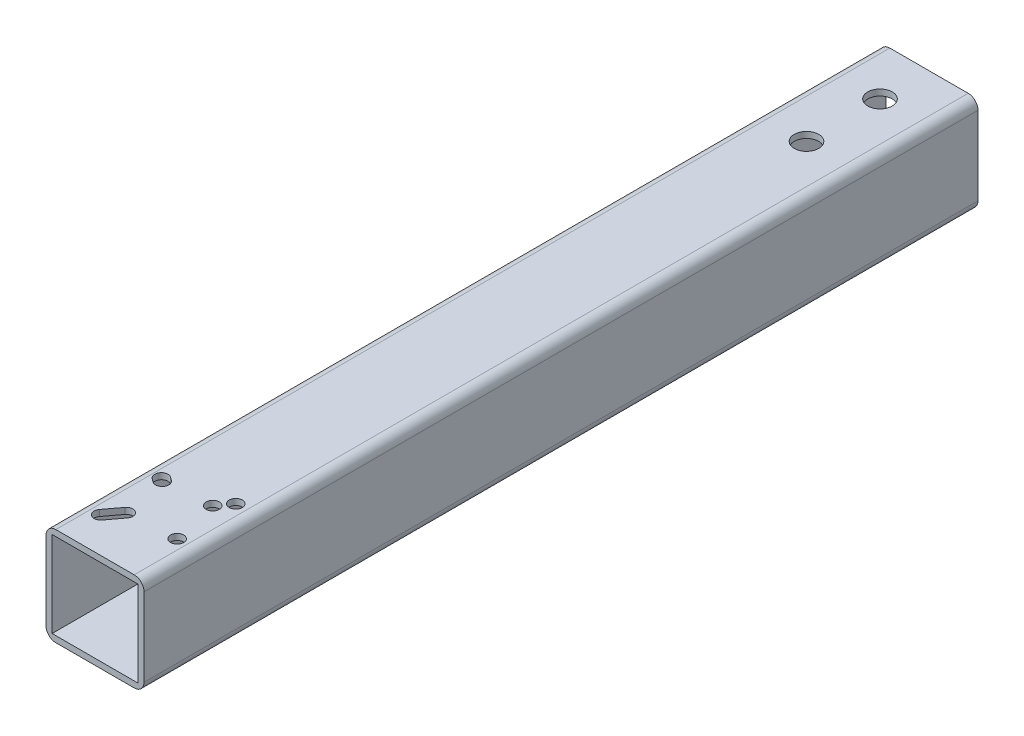
SolidWorks part; units mm, degrees
ref_plane "Front Plane" through (0, 0, 0) normal (0, 0, 1) x (1, 0, 0)
ref_plane "Top Plane" through (0, 0, 0) normal (0, 1, 0) x (1, 0, 0)
ref_plane "Right Plane" through (0, 0, 0) normal (1, 0, 0) x (0, 0, -1)
sketch "Sketch1" plane through (0, 0, 0) normal (0, 0, 1) x (1, 0, 0)
  line L1 (-24.2596, 11.4248) -> (1.1404, 11.4248)
  line L2 (-24.2596, 11.4248) -> (-24.2596, -13.9752)
  line L3 (-24.2596, -13.9752) -> (1.1404, -13.9752)
  line L4 (1.1404, 11.4248) -> (1.1404, -13.9752)
  line L5 (-22.6721, 9.8373) -> (-0.4471, 9.8373)
  line L6 (-22.6721, 9.8373) -> (-22.6721, -12.3877)
  line L7 (-22.6721, -12.3877) -> (-0.4471, -12.3877)
  line L8 (-0.4471, 9.8373) -> (-0.4471, -12.3877)
  dimension "D1" = 25.4
  dimension "D2" = 25.4
  dimension "D3" = 1.5875
  dimension "D4" = 1.5875
  dimension "D5" = 1.5875
  dimension "D6" = 1.5875
extrude "Boss-Extrude1" add sketch "Sketch1" along normal blind 216.154
fillet "Fillet1" radius 2.54 4 edges at (1.1404, -13.9752, 108.077) (-24.2596, -13.9752, 108.077) (-24.2596, 11.4248, 108.077) (1.1404, 11.4248, 108.077)
sketch "Sketch2" plane through (0, 11.4248, 0) normal (0, 1, 0) x (1, 0, 0)
  line L0 (-1.3996, 0) -> (-21.7196, 0) construction
  line L1 (0, 0) -> (0, -59.7417) construction
  line L2 (-11.5596, -12.7) -> (-11.5596, 0) construction
  line L3 (-1.3996, -216.154) -> (-1.3996, 0) construction
  circle A0 centre (-11.5596, -12.7) radius 3.175
  circle A2 centre (-11.5596, -31.75) radius 3.175
  dimension "D1" = 6.35
  dimension "D2" = 12.7
  dimension "D3" = 6.35
  dimension "D6" = 19.05
extrude "Cut-Extrude1" cut sketch "Sketch2" against normal through all
sketch "Sketch3" plane through (0, 11.4248, 0) normal (0, 1, 0) x (1, 0, 0)
  line L0 (-11.5596, -196.85) -> (-15.3182, -171.7296) construction
  line L1 (-11.5596, -196.85) -> (13.426, -193.1116) construction
  line L2 (-11.5596, -196.85) -> (-29.2422, -183.7702) construction
  line L3 (-11.5596, -196.85) -> (2.8538, -177.7228) construction
  line L4 (-11.5596, -12.7) -> (-11.5596, -270.3313) construction
  line L5 (-16.3741, -203.2391) -> (-19.2175, -207.0124) construction
  line L6 (-15.0164, -204.2622) -> (-17.8598, -208.0355)
  line L7 (-17.7318, -202.216) -> (-20.5752, -205.9893)
  line L8 (-19.6056, -190.8984) -> (-18.7888, -191.5026) construction
  line L9 (-18.5946, -189.5316) -> (-17.7778, -190.1358)
  line L10 (-20.6166, -192.2651) -> (-19.7997, -192.8693)
  line L11 (-11.5596, -196.85) -> (30.1254, -196.85) construction
  line L13 (-1.3996, 0) -> (-21.7196, 0) construction
  circle A0 centre (-6.7451, -190.4609) radius 1.7
  circle A1 centre (-4.1721, -187.0465) radius 1.7
  circle A3 centre (-3.922, -202.4995) radius 1.7
  arc A4 (-18.5946, -189.5316) -> (-20.6166, -192.2651) centre (-19.6056, -190.8984) ccw
  arc A5 (-19.7997, -192.8693) -> (-17.7778, -190.1358) centre (-18.7888, -191.5026) ccw
  arc A6 (-15.0164, -204.2622) -> (-17.7318, -202.216) centre (-16.3741, -203.2391) ccw
  arc A7 (-20.5752, -205.9893) -> (-17.8598, -208.0355) centre (-19.2175, -207.0124) ccw
  point P17 (-11.5596, -196.9907)
  point P21 (-17.7958, -205.1258)
  point P27 (-19.1972, -191.2005)
  point P33 (-11.5596, 0)
  point P34 (-20.2082, -192.5672)
  point P35 (0, 0)
  dimension "D1" = 196.85
  dimension "D2" = 3.4
  dimension "D3" = 3.4
  dimension "D4" = 3.4
  dimension "D5" = 3.4
  dimension "D6" = 3.4
  dimension "D7" = 16
  dimension "D8" = 25
  dimension "D9" = 19
  dimension "D10" = 8
  dimension "D11" = 9.5
  dimension "D12" = 9.5
extrude "Cut-Extrude2" cut sketch "Sketch3" against normal blind 2.54
